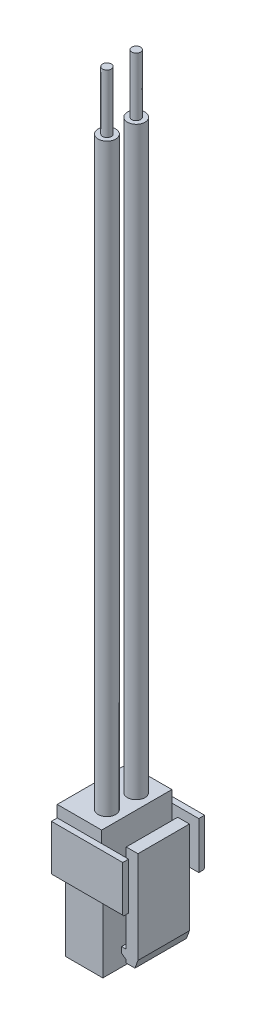
SolidWorks part; units mm, degrees
ref_plane "Front" through (0, 0, 0) normal (0, 0, 1) x (1, 0, 0)
ref_plane "Top" through (0, 0, 0) normal (0, 1, 0) x (1, 0, 0)
ref_plane "Right" through (0, 0, 0) normal (1, 0, 0) x (0, 0, -1)
sketch "Sketch1" plane through (0, 0, 0) normal (0, 1, 0) x (1, 0, 0)
  line L0 (3.9, 3) -> (3.9, 3.5)
  line L1 (-2.2, -3.5) -> (3.9, -3.5)
  line L2 (-2.2, -3.5) -> (-2.2, 3.5)
  line L3 (-2.2, 3.5) -> (3.9, 3.5)
  line L4 (3.9, -3.5) -> (3.9, -3)
  line L8 (1.6, -3) -> (1.6, 3)
  line L9 (0, 0) -> (7.5061, 0) construction
  line L10 (3.9, -3) -> (1.6, -3)
  line L12 (3.9, 3) -> (1.6, 3)
  dimension "D1" = 7
  dimension "D2" = 6.1
  dimension "D3" = 1.6
  dimension "D4" = 2.2
  dimension "D6" = 0.5
extrude "Base-Extrude" add sketch "Sketch1" along normal blind 4
sketch "Sketch2" plane through (0, 4, 0) normal (0, 1, 0) x (-1, 0, 0)
  line L0 (-1.6, 3) -> (-1.6, -3) construction
  line L1 (-1.6, 3) -> (-1.6, -3)
  line L2 (2.2, 3) -> (2.2, -3)
  line L3 (2.2, -3.5) -> (2.2, 3.5) construction
  line L4 (-1.6, -3) -> (-3.9, -3) construction
  line L5 (-3.9, 3) -> (-1.6, 3) construction
  line L6 (0, 0) -> (-6.1712, 0) construction
  line L7 (2.2, 3) -> (-1.6, 3)
  line L8 (2.2, -3) -> (-1.6, -3)
extrude "Boss-Extrude1" add sketch "Sketch2" along normal blind 1
sketch "Sketch3" plane through (0, 0, 0) normal (0, -1, 0) x (1, 0, 0)
  line L0 (1.6, 3) -> (1.6, -3) construction
  line L1 (1.6, -2.9) -> (-1.6, -2.9)
  line L2 (1.6, -2.9) -> (1.6, 2.9)
  line L3 (1.6, 2.9) -> (-1.6, 2.9)
  line L4 (-1.6, -2.9) -> (-1.6, 2.9)
  line L5 (0, 0) -> (-5.1353, 0) construction
  dimension "D1" = 5.8
  dimension "D2" = 3.2
extrude "Boss-Extrude2" add sketch "Sketch3" along normal blind 6
sketch "Sketch4" plane through (0, 0, 0) normal (0, 0, 1) x (1, 0, 0)
  line L0 (1.6, -6) -> (1.6, 0) construction
  line L1 (1.6, 0) -> (1.6, 1)
  line L2 (3.9, 4) -> (3.9, 0) construction
  line L3 (3.9, 4) -> (3.9, -3.9)
  line L4 (3.9, -3.9) -> (3.6452, -4.6)
  line L5 (3.6452, -4.6) -> (2.9, -4.6)
  line L6 (2.9, -4.6) -> (2.9, -4.35)
  line L7 (2.9, -4.35) -> (2.5, -4.0699)
  line L8 (2.5, -4.0699) -> (2.5, -3.5699)
  line L9 (2.5, -3.5699) -> (2.9, -3.5699)
  line L10 (2.9, -3.5699) -> (2.9, 0)
  line L11 (2.9, 0) -> (1.6, 0)
  line L12 (2.9, 1) -> (1.6, 1)
  line L13 (3.9, 4) -> (2.9, 4)
  line L14 (2.9, 4) -> (2.9, 1)
  line L15 (3.9, 0) -> (1.6, 0) construction
  dimension "D1" = 1
  dimension "D2" = 1
  dimension "D3" = 0.7
  dimension "D4" = 20
  dimension "D5" = 8.6
  dimension "D6" = 0.25
  dimension "D7" = 125
  dimension "D8" = 0.5
  dimension "D9" = 0.4
extrude "Boss-Extrude3" add sketch "Sketch4" along normal mid plane 4.4
sketch "Wire Insulation Sketch" plane through (0, 5, 0) normal (0, 1, 0) x (-1, 0, 0)
  line L0 (0, 0) -> (2.5976, 0) construction
  line L1 (2.2, -3) -> (2.2, 3) construction
  circle A0 centre (-0.3, 1.25) radius 0.75
  circle A1 centre (-0.3, -1.25) radius 0.75
  dimension "D2" = 1.5
  dimension "D1" = 2.5
  dimension "D3" = 2.5
extrude "Wire Insulation" add sketch "Wire Insulation Sketch" along normal blind 50
sketch "Wire Sketch" plane through (0, 55, 0) normal (0, 1, 0) x (-1, 0, 0)
  circle A0 centre (-0.3, -1.25) radius 0.375
  circle A1 centre (-0.3, 1.25) radius 0.375
  dimension "D1" = 0.75
extrude "Wire" add sketch "Wire Sketch" along normal blind 5
chamfer "Chamfer1" distance 0.1 angle 45 3 edges at (0.85, 0, 3.5) (-2.2, 0, 0) (0.85, 0, -3.5)
